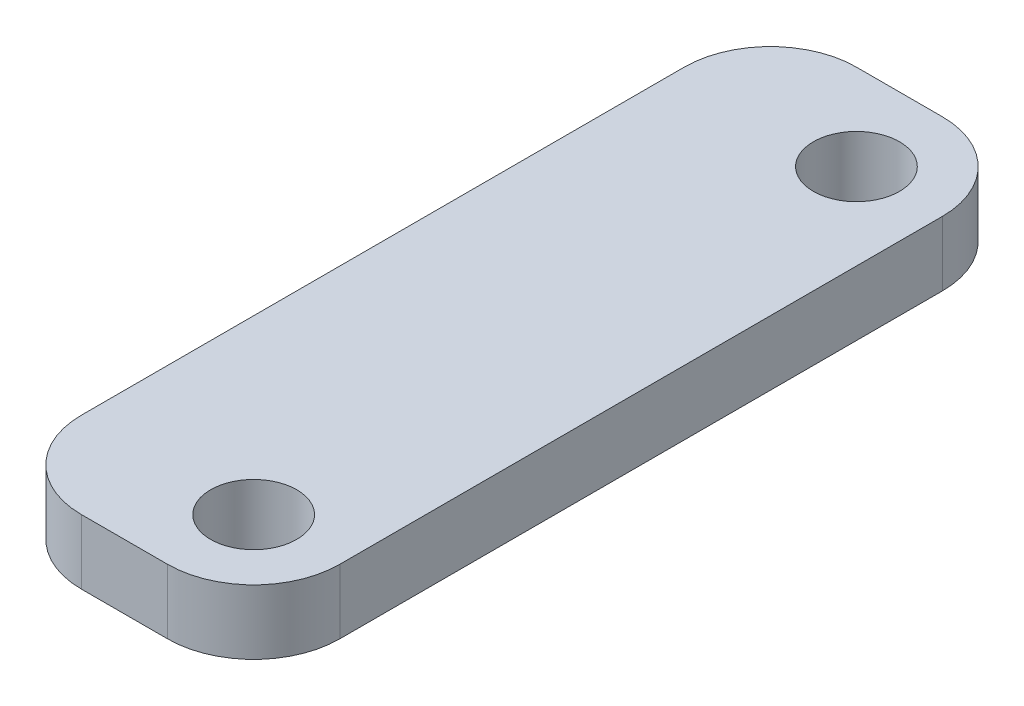
SolidWorks part; units mm, degrees
ref_plane "Front Plane" through (0, 0, 0) normal (0, 0, 1) x (1, 0, 0)
ref_plane "Top Plane" through (0, 0, 0) normal (0, 1, 0) x (1, 0, 0)
ref_plane "Right Plane" through (0, 0, 0) normal (1, 0, 0) x (0, 0, -1)
sketch "Sketch1" plane through (0, 0, 0) normal (0, 1, 0) x (1, 0, 0)
  line L0 (-6, 0) -> (6, 0) construction
  line L1 (-6, -18) -> (6, -18)
  line L2 (-6, -18) -> (-6, 18)
  line L3 (-6, 18) -> (6, 18)
  line L4 (6, -18) -> (6, 18)
  line L5 (-6, -18) -> (6, 18) construction
  line L6 (-6, 18) -> (6, -18) construction
  line L7 (2, 18) -> (2, -18) construction
  circle A0 centre (2, 14) radius 2
  circle A1 centre (2, -14) radius 2
  point P0 (0, 0)
  dimension "D4" = 4
  dimension "D5" = 28
  dimension "D1" = 36
  dimension "D2" = 12
  dimension "D3" = 4
extrude "Boss-Extrude1" add sketch "Sketch1" along normal mid plane 3
fillet "Fillet1" radius 4 4 edges at (-6, 0, -18) (6, 0, -18) (-6, 0, 18) (6, 0, 18)
